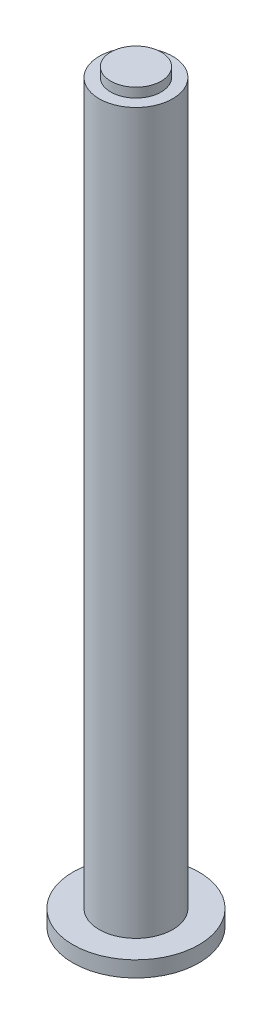
SolidWorks part; units mm, degrees
ref_plane "Front Plane" through (0, 0, 0) normal (0, 0, 1) x (1, 0, 0)
ref_plane "Top Plane" through (0, 0, 0) normal (0, 1, 0) x (1, 0, 0)
ref_plane "Right Plane" through (0, 0, 0) normal (1, 0, 0) x (0, 0, -1)
other "Configuration Table"
sketch "Sketch1" plane through (0, 0, 0) normal (0, 1, 0) x (1, 0, 0)
  circle A0 centre (0, 0) radius 12
extrude "Foot_Flange" add sketch "Sketch1" along normal blind 3
sketch "Sketch2" plane through (0, 0, 0) normal (0, 1, 0) x (1, 0, 0)
  circle A0 centre (0, 0) radius 7
  dimension "D1" = 14
extrude "Leg" add sketch "Sketch2" along normal blind 140
sketch "Sketch3" plane through (0, 0, 0) normal (0, 1, 0) x (1, 0, 0)
  circle A0 centre (0, 0) radius 4.8
extrude "Spigot" add sketch "Sketch3" along normal blind 1.8 from offset 140
equation "\"leg_H\"= 140.0   'ASSUMPTION: Standoff leg height: enclosure floor sits above jar tops (designer choice)"
equation "\"leg_D\"= 14.0   'ASSUMPTION: Standoff leg diameter (designer choice)"
equation "\"D1@Sketch2\" = \"leg_D\""
equation "\"D1@Leg\" = \"leg_H\""
